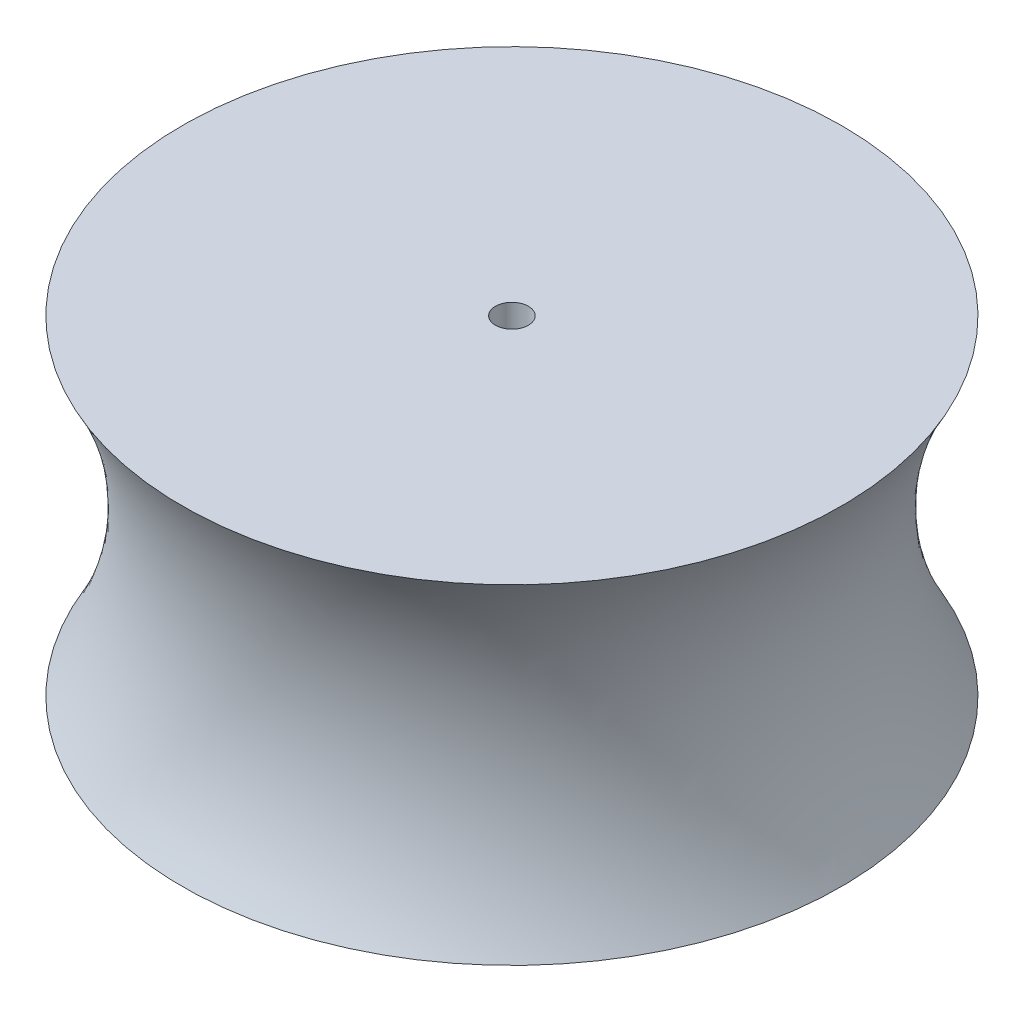
SolidWorks part; units mm, degrees
ref_plane "Front Plane" through (0, 0, 0) normal (0, 0, 1) x (1, 0, 0)
ref_plane "Top Plane" through (0, 0, 0) normal (0, 1, 0) x (1, 0, 0)
ref_plane "Right Plane" through (0, 0, 0) normal (1, 0, 0) x (0, 0, -1)
sketch "Sketch1" plane through (0, 0, 0) normal (0, 1, 0) x (1, 0, 0)
  circle A0 centre (0, 0) radius 20
  dimension "D1" = 40
extrude "Boss-Extrude1" add sketch "Sketch1" along normal blind 20
sketch "Sketch2" plane through (0, 0, 0) normal (1, 0, 0) x (0, 0, -1)
  line L0 (0, 0) -> (0, 20) construction
  line L1 (20, 20) -> (-20, 20) construction
  circle A0 centre (37.3205, 10) radius 20
  dimension "D1" = 40
revolve "Cut-Revolve1" cut sketch "Sketch2" angle 360 about L0
sketch "Sketch3" plane through (0, 20, 0) normal (0, 1, 0) x (1, 0, 0)
  circle A0 centre (0, 0) radius 1
  dimension "D1" = 2
extrude "Cut-Extrude1" cut sketch "Sketch3" against normal through all
